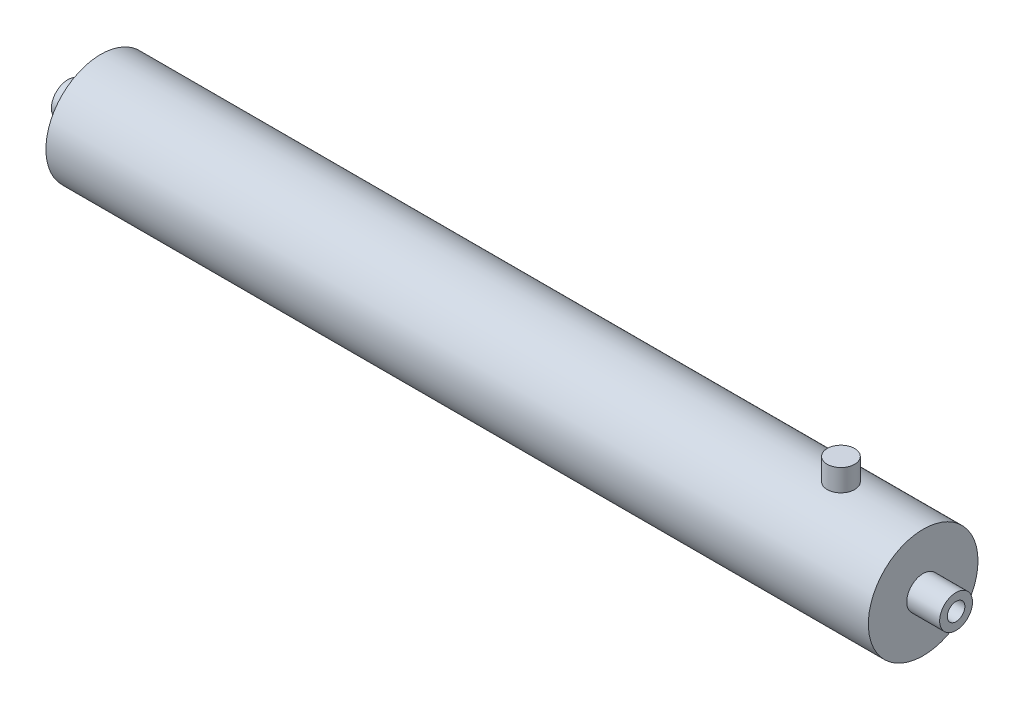
SolidWorks part; units mm, degrees
ref_plane "Front Plane" through (0, 0, 0) normal (0, 0, 1) x (1, 0, 0)
ref_plane "Top Plane" through (0, 0, 0) normal (0, 1, 0) x (1, 0, 0)
ref_plane "Right Plane" through (0, 0, 0) normal (1, 0, 0) x (0, 0, -1)
other "Configuration Table"
sketch "Sketch1" plane through (0, 0, 0) normal (1, 0, 0) x (0, 0, -1)
  circle A0 centre (0, 0) radius 20
  dimension "D1" = 40
extrude "Body" add sketch "Sketch1" along normal blind 300 from offset 150
sketch "Sketch2" plane through (0, 0, 0) normal (1, 0, 0) x (0, 0, -1)
  circle A0 centre (0, 0) radius 6
  dimension "D1" = 12
extrude "Inlet_Port" add sketch "Sketch2" along normal blind 12 from offset 162
sketch "Sketch3" plane through (0, 0, 0) normal (1, 0, 0) x (0, 0, -1)
  circle A0 centre (0, 0) radius 3.2
  dimension "D1" = 6.4
extrude "Inlet_Socket" cut sketch "Sketch3" along normal blind 10 from offset 162
sketch "Sketch4" plane through (0, 0, 0) normal (1, 0, 0) x (0, 0, -1)
  circle A0 centre (0, 0) radius 6
  dimension "D1" = 12
extrude "Outlet_Port" add sketch "Sketch4" along normal blind 12 from offset 150
sketch "Sketch5" plane through (0, 0, 0) normal (1, 0, 0) x (0, 0, -1)
  circle A0 centre (0, 0) radius 3.2
  dimension "D1" = 6.4
extrude "Outlet_Socket" cut sketch "Sketch5" against normal blind 10 from offset 162
sketch "Sketch6" plane through (0, 0, 0) normal (0, 1, 0) x (1, 0, 0)
  circle A0 centre (120, 0) radius 5
  dimension "D1" = 10
extrude "Lamp_Cable_Gland" add sketch "Sketch6" along normal blind 8 from offset 20
equation "\"Jar_OD\"= 90  'ASSUMED - Part G fallback - jar outer diameter"
equation "\"Jar_H\"= 120  'ASSUMED - Part G fallback - jar height"
equation "\"Pump_L\"= 45  'ASSUMED - Part G fallback"
equation "\"Pump_W\"= 24  'ASSUMED - Part G fallback"
equation "\"Pump_H\"= 33  'ASSUMED - Part G fallback"
equation "\"Pump_Outlet_OD\"= 7.5  'ASSUMED - Part G fallback"
equation "\"Tube_OD\"= 8  'ASSUMED - Part G fallback"
equation "\"Tube_ID\"= 6  'ASSUMED - Part G fallback"
equation "\"TDS_Body_Dia\"= 12  'ASSUMED - Part G fallback"
equation "\"TDS_Wet_Len\"= 45  'ASSUMED - Part G fallback - length in water"
equation "\"DS_Tube_Dia\"= 6  'ASSUMED - Part G fallback"
equation "\"DS_Tube_Len\"= 50  'ASSUMED - Part G fallback"
equation "\"ORP_Body_Dia\"= 12  'ASSUMED - Part G fallback"
equation "\"ORP_Body_Len\"= 150  'ASSUMED - Part G fallback"
equation "\"ORP_Cap_Dia\"= 16  'ASSUMED - Part G fallback"
equation "\"Turb_W\"= 33  'ASSUMED - Part G fallback - head width"
equation "\"Turb_D\"= 28  'ASSUMED - Part G fallback - head depth"
equation "\"Turb_H\"= 30  'ASSUMED - Part G fallback - head height"
equation "\"Turb_Slot_W\"= 10  'ASSUMED - Part G fallback - slot width"
equation "\"Flow_L\"= 62  'ASSUMED - Part G fallback YF-S201"
equation "\"Flow_W\"= 36  'ASSUMED - Part G fallback"
equation "\"Flow_H\"= 35  'ASSUMED - Part G fallback"
equation "\"Thread_G12_OD\"= 20.955  'ASSUMED - Part G fallback thread G1/2 (major diameter)"
equation "\"Valve_L\"= 75  'ASSUMED - Part G fallback"
equation "\"Valve_W\"= 45  'ASSUMED - Part G fallback"
equation "\"Valve_H\"= 60  'ASSUMED - Part G fallback"
equation "\"Tee_L\"= 40  'ASSUMED - Part G fallback - overall length"
equation "\"Tee_Branch_L\"= 25  'ASSUMED - Part G fallback"
equation "\"Tee_OD\"= 12  'ASSUMED - Part G fallback"
equation "\"LED_Board_L\"= 20  'ASSUMED - Part G fallback"
equation "\"LED_Board_W\"= 20  'ASSUMED - Part G fallback - LED at centre"
equation "\"GUVA_L\"= 20  'ASSUMED - Part G fallback"
equation "\"GUVA_W\"= 12  'ASSUMED - Part G fallback - sensor at centre"
equation "\"Reed_L\"= 27  'ASSUMED - Part G fallback MC-38 half"
equation "\"Reed_W\"= 14  'ASSUMED - Part G fallback"
equation "\"Reed_H\"= 8  'ASSUMED - Part G fallback"
equation "\"ESP_L\"= 51  'ASSUMED - Part G fallback"
equation "\"ESP_W\"= 28  'ASSUMED - Part G fallback"
equation "\"TFT_L\"= 58  'ASSUMED - Part G fallback - board"
equation "\"TFT_W\"= 35  'ASSUMED - Part G fallback - board"
equation "\"TFT_Win_L\"= 35  'ASSUMED - Part G fallback - visible window"
equation "\"TFT_Win_W\"= 28  'ASSUMED - Part G fallback - visible window"
equation "\"Relay_L\"= 50  'ASSUMED - Part G fallback"
equation "\"Relay_W\"= 26  'ASSUMED - Part G fallback"
equation "\"Relay_H\"= 19  'ASSUMED - Part G fallback"
equation "\"Mosfet_L\"= 34  'ASSUMED - Part G fallback"
equation "\"Mosfet_W\"= 17  'ASSUMED - Part G fallback"
equation "\"Mosfet_H\"= 12  'ASSUMED - Part G fallback"
equation "\"TDS_Board_L\"= 42  'ASSUMED - Part G fallback"
equation "\"TDS_Board_W\"= 32  'ASSUMED - Part G fallback"
equation "\"Turb_Board_L\"= 38  'ASSUMED - Part G fallback"
equation "\"Turb_Board_W\"= 28  'ASSUMED - Part G fallback"
equation "\"BNC_Thread_Dia\"= 9.5  'ASSUMED - Part G fallback"
equation "\"Plate_L\"= 420  'ASSUMED - Part G fallback"
equation "\"Plate_W\"= 297  'ASSUMED - Part G fallback"
equation "\"Plate_T\"= 6  'ASSUMED - Part G fallback"
equation "\"Booster_L\"= 150  'ASSUMED - Part G fallback - booster pump"
equation "\"Booster_W\"= 95  'ASSUMED - Part G fallback"
equation "\"Booster_H\"= 100  'ASSUMED - Part G fallback"
equation "\"PTube_OD\"= 6.35  'ASSUMED - Part G fallback - product tube 1/4 inch"
equation "\"Qz_Out\"= 12  'ASSUMED - Part G fallback - quartz channel outside square"
equation "\"Qz_Path\"= 10  'ASSUMED - Part G fallback - quartz channel inside light path"
equation "\"Qz_L\"= 40  'ASSUMED - Part G fallback - quartz channel length"
equation "\"LED860_Dia\"= 5  'ASSUMED - Part G fallback - 860 nm LED"
equation "\"BPW_L\"= 5.4  'ASSUMED - Part G fallback - BPW34"
equation "\"BPW_W\"= 4.3  'ASSUMED - Part G fallback - BPW34"
equation "\"Cart_Dia\"= 50  'ASSUMED - Part G fallback - sediment and pre-carbon cartridges"
equation "\"Cart_L\"= 255  'ASSUMED - Part G fallback"
equation "\"UF_Dia\"= 50  'ASSUMED - Part G fallback - UF cartridge"
equation "\"UF_L\"= 260  'ASSUMED - Part G fallback"
equation "\"RO_Dia\"= 62  'ASSUMED - Part G fallback - RO membrane housing"
equation "\"RO_L\"= 300  'ASSUMED - Part G fallback"
equation "\"UVC_Dia\"= 40  'ASSUMED - Part G fallback - UV-C chamber"
equation "\"UVC_L\"= 300  'ASSUMED - Part G fallback"
equation "\"Tank_W\"= 260  'ASSUMED - Part G fallback - storage tank"
equation "\"Tank_D\"= 160  'ASSUMED - Part G fallback"
equation "\"Tank_H\"= 300  'ASSUMED - Part G fallback"
equation "\"Cab_W\"= 400  'ASSUMED - Part G fallback - purifier cabinet"
equation "\"Cab_D\"= 270  'ASSUMED - Part G fallback"
equation "\"Cab_H\"= 560  'ASSUMED - Part G fallback"
equation "\"ORP_Board_L\"= 40  'ASSUMED - Part G fallback - ORP buffer board"
equation "\"ORP_Board_W\"= 30  'ASSUMED - Part G fallback"
equation "\"Opt_Board_L\"= 50  'ASSUMED - Part G fallback - optical front-end board"
equation "\"Opt_Board_W\"= 40  'ASSUMED - Part G fallback"
equation "\"Buck_L\"= 43  'ASSUMED - Part G fallback - 12 V to 5 V buck module"
equation "\"Buck_W\"= 21  'ASSUMED - Part G fallback"
equation "\"Buck_H\"= 14  'ASSUMED - Part G fallback"
equation "\"BB_L\"= 165  'ASSUMED - Part G fallback - breadboard (As_Built_R3 only)"
equation "\"BB_W\"= 55  'ASSUMED - Part G fallback"
equation "\"BB_H\"= 10  'ASSUMED - Part G fallback"
equation "\"Cuv_W\"= 12.5  'ASSUMED - old R3 cuvette (station suppressed in SS4)"
equation "\"Cuv_D\"= 12.5  'ASSUMED - old R3 cuvette (station suppressed in SS4)"
equation "\"Cuv_H\"= 45  'ASSUMED - old R3 cuvette (station suppressed in SS4)"
equation "\"Probe_Clr\"= 0.3  'DESIGN VALUE - Part C rule 3 - printed probe hole = diameter + 0.3"
equation "\"Label_H\"= 0.6  'DESIGN VALUE - Part D - raised label height"
